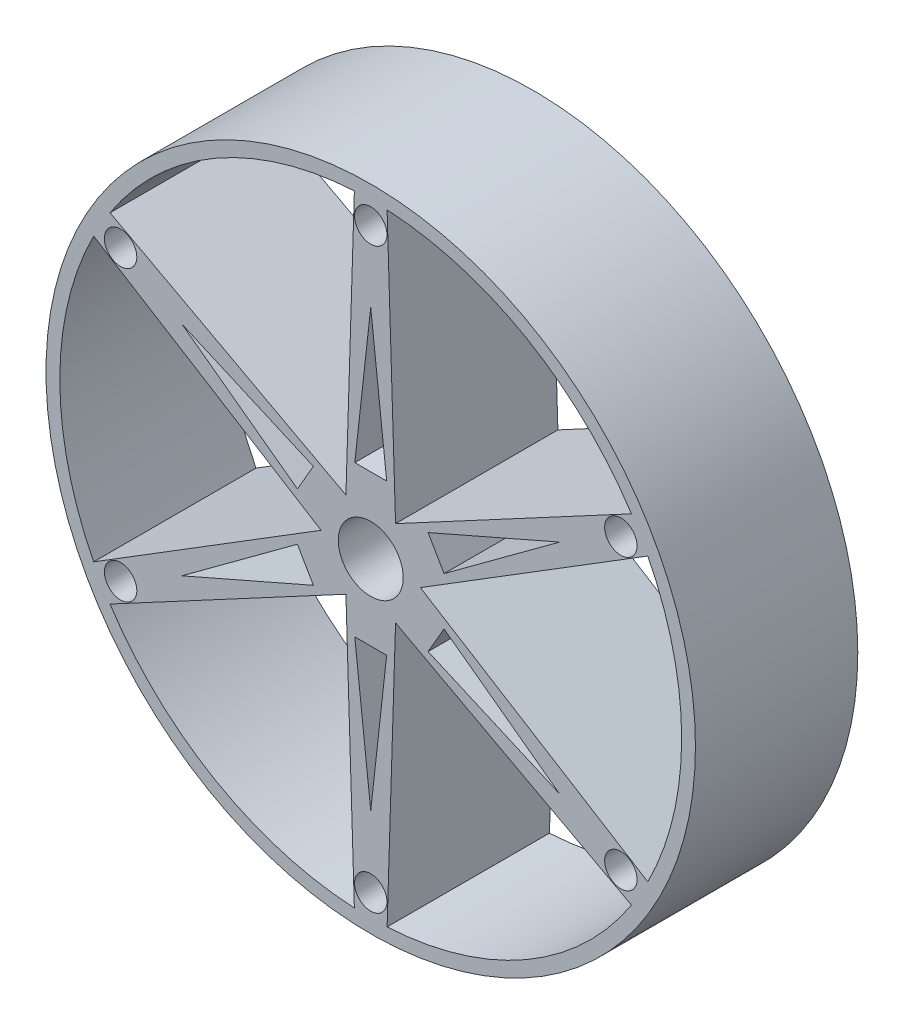
SolidWorks part; units mm, degrees
material "PBTP"
ref_plane "Спереди" through (0, 0, 0) normal (0, 0, 1) x (1, 0, 0)
ref_plane "Сверху" through (0, 0, 0) normal (0, 1, 0) x (1, 0, 0)
ref_plane "Справа" through (0, 0, 0) normal (1, 0, 0) x (0, 0, -1)
sketch "Sketch1" plane through (0, 0, 0) normal (0, 0, 1) x (1, 0, 0)
  line L0 (0, 3) -> (0, 0) construction
  line L1 (0.1472, 2.9964) -> (0.2359, 0.1853)
  line L2 (-0.1472, 2.9964) -> (-0.2359, 0.1853)
  line L3 (2.5213, 1.6257) -> (0.0426, 0.297)
  line L4 (2.6686, 1.3707) -> (0.2785, -0.1116)
  line L5 (2.6686, -1.3707) -> (0.2785, 0.1116)
  line L6 (2.5213, -1.6257) -> (0.0426, -0.297)
  line L7 (0.1472, -2.9964) -> (0.2359, -0.1853)
  line L8 (-0.1472, -2.9964) -> (-0.2359, -0.1853)
  line L9 (-2.5213, -1.6257) -> (-0.0426, -0.297)
  line L10 (-2.6686, -1.3707) -> (-0.2785, 0.1116)
  line L11 (-2.6686, 1.3707) -> (-0.2785, -0.1116)
  line L12 (-2.5213, 1.6257) -> (-0.0426, 0.297)
  line L13 (0, 2.0149) -> (0.1472, 0.697)
  line L14 (0.1472, 0.697) -> (-0.1472, 0.697)
  line L15 (-0.1472, 0.697) -> (0, 2.0149)
  line L16 (0.53, 0.476) -> (1.745, 1.0075)
  line L17 (0.6773, 0.221) -> (0.53, 0.476)
  line L18 (1.745, 1.0075) -> (0.6773, 0.221)
  line L19 (0.6773, -0.221) -> (1.745, -1.0075)
  line L20 (0.53, -0.476) -> (0.6773, -0.221)
  line L21 (1.745, -1.0075) -> (0.53, -0.476)
  line L22 (0.1472, -0.697) -> (0, -2.0149)
  line L23 (-0.1472, -0.697) -> (0.1472, -0.697)
  line L24 (0, -2.0149) -> (-0.1472, -0.697)
  line L25 (-0.53, -0.476) -> (-1.745, -1.0075)
  line L26 (-0.6773, -0.221) -> (-0.53, -0.476)
  line L27 (-1.745, -1.0075) -> (-0.6773, -0.221)
  line L28 (-0.6773, 0.221) -> (-1.745, 1.0075)
  line L29 (-0.53, 0.476) -> (-0.6773, 0.221)
  line L30 (-1.745, 1.0075) -> (-0.53, 0.476)
  circle A0 centre (0, 0) radius 3
  circle A1 centre (0, 0) radius 0.3
  circle A2 centre (0, 0) radius 2.8726
  circle A3 centre (0, 2.6684) radius 0.1498
  circle A4 centre (2.3109, 1.3342) radius 0.1498
  circle A5 centre (2.3109, -1.3342) radius 0.1498
  circle A6 centre (0, -2.6684) radius 0.1498
  circle A7 centre (-2.3109, -1.3342) radius 0.1498
  circle A8 centre (-2.3109, 1.3342) radius 0.1498
  point P31 (0, 0)
  point P64 (0, 0)
  dimension "D1" = 6
  dimension "D2" = 6
  dimension "D3" = 6
extrude "Boss-Extrude1" add sketch "Sketch1" along normal blind 1.5 contours A2 L2 A0 L12 | L0 A0 L2 A2 | A0 L0 A2 L1 | A2 L3 A0 L1 | A2 L7 A0 L6 | A2 L6 A0 L5 | A2 L5 A0 L4 | A2 L9 A0 L8 | A2 L8 A0 L7 | A2 L10 A0 L9 | A2 L11 A0 L10 | A2 L4 A0 L3 | A2 L12 A0 L11 | L12 A2 L11 L10 A1 L2 A8 L28 L30 L29 | L10 A2 L9 L8 A1 L11 A7 L25 L27 L26 | A1 L10 L11 | A1 L12 L2 | A2 L0 A3 L13 L14 A1 L3 L1 | L0 A2 L2 L12 A1 L14 L15 A3 | A1 L1 L3 | L4 A2 L3 L1 A1 L5 A4 L16 L18 L17 | A1 L4 L5 | L6 A2 L5 L4 A1 L7 A5 L19 L21 L20 | A1 L6 L7 | L8 A2 L7 L6 A1 L9 A6 L22 L24 L23 | A1 L8 L9
